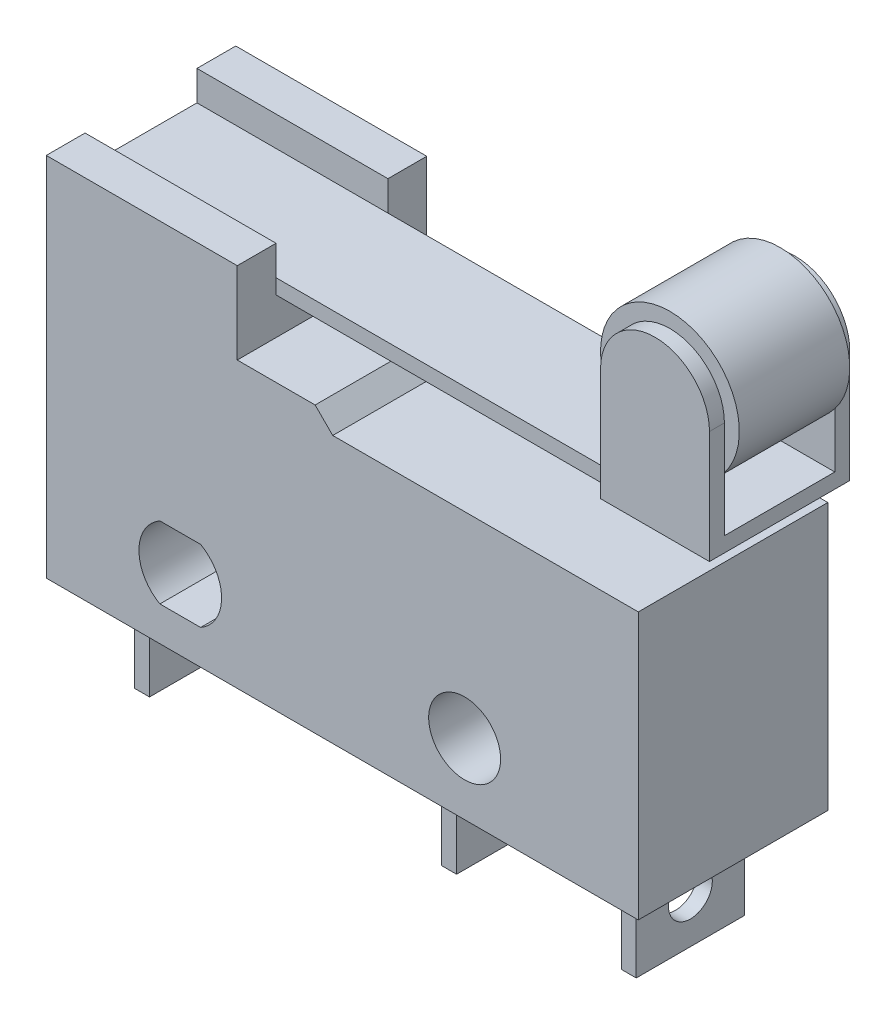
SolidWorks part; units mm, degrees
ref_plane "정면" through (0, 0, 0) normal (0, 0, 1) x (1, 0, 0)
ref_plane "윗면" through (0, 0, 0) normal (0, 1, 0) x (1, 0, 0)
ref_plane "우측면" through (0, 0, 0) normal (1, 0, 0) x (0, 0, -1)
sketch "스케치1" plane through (0, 0, 0) normal (0, 0, 1) x (1, 0, 0)
  line L0 (-10.2128, 1.205) -> (-8.8472, 1.205)
  line L1 (-14.02, -2.36) -> (5.82, -2.36)
  line L2 (-8.8472, -1.205) -> (-10.2128, -1.205)
  line L3 (5.82, -2.36) -> (5.82, 6.58)
  line L4 (5.82, 6.58) -> (-4.42, 6.58)
  line L5 (-14.02, 6.58) -> (-14.02, -2.36)
  line L6 (-4.42, 6.58) -> (-5.01, 7.17)
  line L7 (-5.01, 7.17) -> (-7.62, 7.17)
  line L8 (-7.62, 7.17) -> (-7.62, 9.908)
  line L9 (-7.62, 9.908) -> (-14.02, 9.908)
  line L10 (-14.02, 9.908) -> (-14.02, 6.58)
  circle A0 centre (0, 0) radius 1.205
  arc A1 (-10.2128, 1.205) -> (-10.2128, -1.205) centre (-9.53, 0) ccw
  arc A2 (-8.8472, -1.205) -> (-8.8472, 1.205) centre (-9.53, 0) ccw
  dimension "D1" = 2.41
  dimension "D2" = 2.77
  dimension "D3" = 2.41
  dimension "D4" = 1.205
  dimension "D5" = 9.53
  dimension "D6" = 2.36
  dimension "D7" = 8.94
  dimension "D8" = 9.53
  dimension "D9" = 12.268
  dimension "D10" = 19.84
  dimension "D11" = 7.62
  dimension "D12" = 6.4
  dimension "D13" = 45
  dimension "D14" = 9.6
extrude "보스-돌출1" add sketch "스케치1" along normal mid plane 6.35
sketch "스케치2" plane through (0, -2.36, 0) normal (0, -1, 0) x (1, 0, 0)
  line L0 (-14.02, 3.175) -> (-14.02, -3.175) construction
  line L1 (-12.42, 1.815) -> (-11.92, 1.815)
  line L2 (-12.42, 1.815) -> (-12.42, -1.815)
  line L3 (-12.42, -1.815) -> (-11.92, -1.815)
  line L4 (-11.92, 1.815) -> (-11.92, -1.815)
  line L5 (-2.13, 1.815) -> (-1.63, 1.815)
  line L6 (-2.13, 1.815) -> (-2.13, -1.815)
  line L7 (-2.13, -1.815) -> (-1.63, -1.815)
  line L8 (-1.63, 1.815) -> (-1.63, -1.815)
  line L9 (3.89, 1.815) -> (4.39, 1.815)
  line L10 (3.89, 1.815) -> (3.89, -1.815)
  line L11 (3.89, -1.815) -> (4.39, -1.815)
  line L12 (4.39, 1.815) -> (4.39, -1.815)
  point P12 (-12.17, 1.815)
  point P13 (-1.88, 1.815)
  point P14 (4.14, 1.815)
  point P17 (-12.42, 0)
  point P18 (-2.13, 0)
  point P19 (3.89, 0)
  dimension "D1" = 0.5
  dimension "D2" = 0.5
  dimension "D3" = 0.5
  dimension "D4" = 3.63
  dimension "D5" = 3.63
  dimension "D6" = 3.63
  dimension "D7" = 1.85
  dimension "D8" = 10.29
  dimension "D9" = 6.02
extrude "보스-돌출2" add sketch "스케치2" along normal blind 3.08
sketch "스케치3" plane through (-12.42, 0, 0) normal (-1, 0, 0) x (0, 0, 1)
  line L0 (-1.815, -3.9) -> (1.815, -3.9) construction
  line L1 (-1.815, -5.44) -> (-1.815, -2.36) construction
  line L2 (1.815, -5.44) -> (1.815, -2.36) construction
  circle A0 centre (0, -3.9) radius 0.735
  dimension "D1" = 1.47
extrude "컷-돌출1" cut sketch "스케치3" against normal through all
sketch "스케치4" plane through (0, 9.908, 0) normal (0, 1, 0) x (1, 0, 0)
  line L0 (-14.02, -3.175) -> (-14.02, 3.175) construction
  line L1 (-14.02, 1.875) -> (-7.62, 1.875)
  line L2 (-14.02, 1.875) -> (-14.02, -1.875)
  line L3 (-14.02, -1.875) -> (-7.62, -1.875)
  line L4 (-7.62, 1.875) -> (-7.62, -1.875)
  line L5 (-7.62, -3.175) -> (-7.62, 3.175) construction
  line L6 (-7.62, 3.175) -> (-14.02, 3.175) construction
  line L7 (-7.62, -3.175) -> (-14.02, -3.175) construction
  dimension "D1" = 1.3
  dimension "D2" = 1.3
extrude "컷-돌출2" cut sketch "스케치4" against normal blind 1
sketch "스케치6" plane through (0, 8.908, 0) normal (0, 1, 0) x (1, 0, 0)
  line L1 (-14.02, 1.875) -> (7.38, 1.875)
  line L2 (-14.02, 1.875) -> (-14.02, -1.875)
  line L3 (-14.02, -1.875) -> (7.38, -1.875)
  line L4 (7.38, 1.875) -> (7.38, -1.875)
  dimension "D1" = 21.4
extrude "보스-돌출3" add sketch "스케치6" against normal blind 0.5
sketch "스케치7" plane through (0, 8.908, 0) normal (0, 1, 0) x (1, 0, 0)
  line L0 (7.38, -1.875) -> (7.38, 1.875) construction
  line L1 (3.73, 2.35) -> (7.38, 2.35)
  line L2 (3.73, 2.35) -> (3.73, -2.35)
  line L3 (3.73, -2.35) -> (7.38, -2.35)
  line L4 (7.38, 2.35) -> (7.38, -2.35)
  point P4 (7.38, 0)
  dimension "D1" = 4.7
  dimension "D2" = 3.65
extrude "보스-돌출4" add sketch "스케치7" against normal blind 0.5
sketch "스케치8" plane through (0, 0, 2.35) normal (0, 0, 1) x (1, 0, 0)
  line L1 (3.73, 8.408) -> (7.38, 8.408)
  line L2 (3.73, 8.408) -> (3.73, 12.183)
  line L4 (7.38, 8.408) -> (7.38, 12.183)
  arc A0 (7.38, 12.183) -> (3.73, 12.183) centre (5.555, 12.183) ccw
  point P8 (5.555, 8.408)
  dimension "D3" = 3.775
extrude "보스-돌출5" add sketch "스케치8" against normal blind 0.5
ref_plane "평면1" through (0, 0, 0) normal (0, 0, 1) x (1, 0, 0)
mirror "대칭 복사1" about plane through (0, 0, 0) normal (0, 0, 1) of "보스-돌출5"
sketch "스케치9" plane through (0, 0, 0) normal (0, 0, 1) x (1, 0, 0)
  circle A0 centre (5.555, 12.183) radius 2.325
  arc A2 (7.38, 12.183) -> (3.73, 12.183) centre (5.555, 12.183) ccw construction
  dimension "D1" = 4.65
extrude "보스-돌출7" add sketch "스케치9" along normal up to surface and the other way up to surface up to face at (5.555, 11.0018, 1.85) other way up to face at (5.555, 11.0018, -1.85)
sketch "Sketch1" [suppressed] plane through (0, 0, 3.175) normal (0, 0, 1) x (1, 0, 0)
  line L0 (-14.02, 9.908) -> (5.555, 9.908) construction
  line L1 (5.555, 9.908) -> (5.555, 14.508) construction
  arc A0 (7.38, 10.7425) -> (3.73, 10.7425) centre (5.555, 12.183) ccw construction
